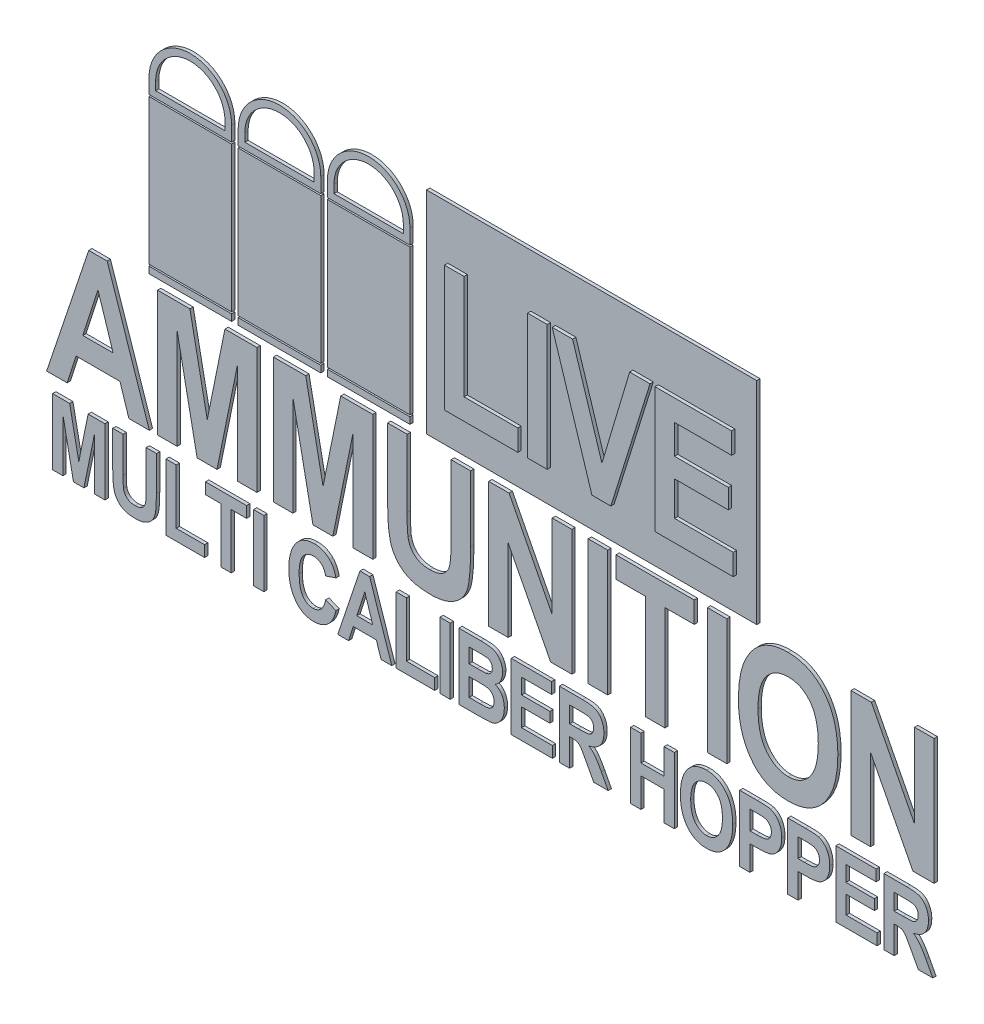
SolidWorks part; units mm, degrees
ref_plane "Front Plane" through (0, 0, 0) normal (0, 0, 1) x (1, 0, 0)
ref_plane "Top Plane" through (0, 0, 0) normal (0, 1, 0) x (1, 0, 0)
ref_plane "Right Plane" through (0, 0, 0) normal (1, 0, 0) x (0, 0, -1)
sketch "Sketch2" plane through (0, 0, 0) normal (0, 0, 1) x (1, 0, 0)
  line L0 (-10.5, 51.5) -> (-10.5, 49)
  line L1 (-12.5, 0) -> (12.5, 0)
  line L2 (-12.5, 0) -> (-12.5, 2)
  line L3 (-12.5, 51.5) -> (12.5, 51.5) construction
  line L4 (12.5, 0) -> (12.5, 2)
  line L5 (-10.5, 49) -> (10.5, 49)
  line L6 (10.5, 49) -> (10.5, 51.5)
  line L7 (12.5, 2.5) -> (12.5, 46.5)
  line L8 (-12.5, 47) -> (12.5, 47)
  line L9 (-12.5, 47) -> (-12.5, 46.5) construction
  line L10 (-12.5, 46.5) -> (12.5, 46.5)
  line L11 (-12.5, 47) -> (-12.5, 51.5)
  line L12 (-12.5, 2) -> (12.5, 2)
  line L13 (12.5, 47) -> (12.5, 51.5)
  line L14 (-12.5, 2.5) -> (12.5, 2.5)
  line L15 (-12.5, 2.5) -> (-12.5, 46.5)
  line L16 (-12.5, 2) -> (-12.5, 2.5) construction
  arc A0 (-12.5, 51.5) -> (12.5, 51.5) centre (0, 51.5) cw
  arc A1 (10.5, 51.5) -> (-10.5, 51.5) centre (0, 51.5) ccw
  dimension "D1" = 25
  dimension "D3" = 2
  dimension "D2" = 64
  dimension "D4" = 13
  dimension "D5" = 0.5
  dimension "D6" = 2
  dimension "D7" = 2
extrude "Boss-Extrude1" add sketch "Sketch2" along normal blind 1 contours A0 L11 L8 L13 A1 L6 L5 L0 | L15 L14 L7 L10 | L12 L2 L1 L4
pattern_linear "LPattern1" count 3 spacing 27 along (1, 0, 0) of bodies 144 143 101
sketch "Sketch3" plane through (0, 0, 0) normal (0, 0, 1) x (1, 0, 0)
  line L1 (71.5, 0) -> (171.5, 0)
  line L2 (71.5, 0) -> (71.5, 64)
  line L3 (71.5, 64) -> (171.5, 64)
  line L4 (171.5, 0) -> (171.5, 64)
  line L6 (66.5, 0) -> (66.5, 2) construction
  line L7 (41.5, 0) -> (66.5, 0) construction
  arc A1 (12.5, 51.5) -> (-12.5, 51.5) centre (0, 51.5) ccw construction
  dimension "D1" = 5
  dimension "D2" = 100
extrude "Boss-Extrude2" add sketch "Sketch3" along normal up to surface (1 mm away) separate body up to face at (0, 24.5, 1)
sketch "Sketch4" plane through (0, 0, 1) normal (0, 0, 1) x (1, 0, 0)
  line L0 (74.5, 10) -> (171.5, 10) construction
  line L1 (-42.5, -40) -> (246.6472, -40) construction
  line L3 (71.5, 0) -> (71.5, 64) construction
  line L4 (171.5, 64) -> (171.5, 0) construction
  line L5 (171.5, 0) -> (71.5, 0) construction
  line L7 (-42.5, -65) -> (248.4737, -65) construction
  line L8 (-42.5, -65) -> (-42.5, -40) construction
  line L9 (71.5, 0) -> (171.5, 0) construction
  line L10 (-12.5, 0) -> (-12.5, 2) construction
  text T0 "<b>LIVE</b>" font "Arial Narrow" height 38
  text T1 "<b>AMMUNITION</b>" font "Arial Narrow" height 38
  text T2 "<b>MULTI CALIBER HOPPER</b>" font "Arial Narrow" height 20
  dimension "D1" = 10
  dimension "D2" = 3
  dimension "D3" = 40
  dimension "D4" = 30
  dimension "D5" = 25
extrude "Boss-Extrude3" add sketch "Sketch4" along normal blind 1
scale "Scale1" bodies to scale 128 126 125 101 111 144 122 146 120 103 110 118 117 107 115 127 121 105 129 102 134 108 116 148 112 145 123 147 109 119 124 113 131 130 106 133 114 143 scale about origin uniform scaling yes scale factor 0.6
